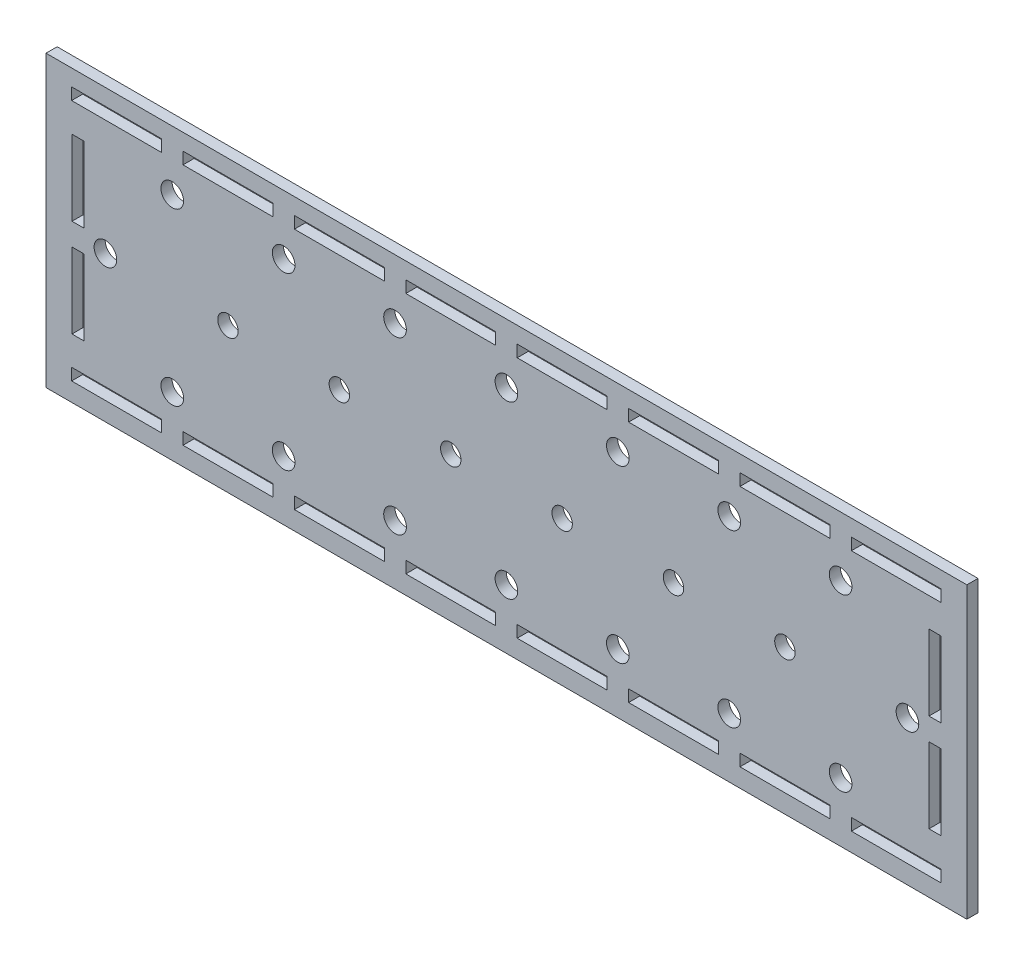
SolidWorks part; units mm, degrees
ref_plane "Front Plane" through (0, 0, 0) normal (0, 0, 1) x (1, 0, 0)
ref_plane "Top Plane" through (0, 0, 0) normal (0, 1, 0) x (1, 0, 0)
ref_plane "Right Plane" through (0, 0, 0) normal (1, 0, 0) x (0, 0, -1)
sketch "Sketch1" plane through (0, 0, 0) normal (0, 0, 1) x (-1, 0, 0)
  line L0 (-395.8872, 493) -> (-395.8872, 489.8)
  line L2 (-395.8872, 493) -> (-371.6872, 493)
  line L3 (-371.6872, 493) -> (-371.6872, 489.8)
  line L4 (-395.8872, 489.8) -> (-371.6872, 489.8)
  line L8 (-425.8872, 493) -> (-425.8872, 489.8)
  line L9 (-552.7872, 498) -> (-304.7872, 498)
  line L10 (-552.7872, 498) -> (-552.7872, 420)
  line L11 (-552.7872, 420) -> (-304.7872, 420)
  line L12 (-304.7872, 498) -> (-304.7872, 420)
  line L13 (-365.8872, 493) -> (-341.6872, 493)
  line L14 (-365.8872, 493) -> (-365.8872, 489.8)
  line L15 (-365.8872, 489.8) -> (-341.6872, 489.8)
  line L16 (-341.6872, 493) -> (-341.6872, 489.8)
  line L17 (-425.8872, 493) -> (-401.6872, 493)
  line L18 (-401.6872, 493) -> (-401.6872, 489.8)
  line L19 (-425.8872, 489.8) -> (-401.6872, 489.8)
  line L20 (-455.8872, 493) -> (-455.8872, 489.8)
  line L21 (-455.8872, 493) -> (-431.6872, 493)
  line L22 (-431.6872, 493) -> (-431.6872, 489.8)
  line L23 (-455.8872, 489.8) -> (-431.6872, 489.8)
  line L24 (-485.8872, 493) -> (-485.8872, 489.8)
  line L25 (-485.8872, 493) -> (-461.6872, 493)
  line L26 (-461.6872, 493) -> (-461.6872, 489.8)
  line L27 (-485.8872, 489.8) -> (-461.6872, 489.8)
  line L28 (-515.8872, 493) -> (-515.8872, 489.8)
  line L29 (-515.8872, 493) -> (-491.6872, 493)
  line L30 (-491.6872, 493) -> (-491.6872, 489.8)
  line L31 (-515.8872, 489.8) -> (-491.6872, 489.8)
  line L32 (-545.8872, 493) -> (-545.8872, 489.8)
  line L33 (-545.8872, 493) -> (-521.6872, 493)
  line L34 (-521.6872, 493) -> (-521.6872, 489.8)
  line L35 (-545.8872, 489.8) -> (-521.6872, 489.8)
  line L36 (-335.8872, 493) -> (-335.8872, 489.8)
  line L37 (-335.8872, 493) -> (-311.6872, 493)
  line L38 (-311.6872, 493) -> (-311.6872, 489.8)
  line L39 (-335.8872, 489.8) -> (-311.6872, 489.8)
  line L40 (-552.7872, 459) -> (-513.2251, 459) construction
  line L73 (-314.9872, 455.7) -> (-311.7872, 455.7)
  line L74 (-314.9872, 482) -> (-311.7872, 482)
  line L75 (-314.9872, 482) -> (-314.9872, 461.7)
  line L76 (-314.9872, 461.7) -> (-311.7872, 461.7)
  line L77 (-311.7872, 482) -> (-311.7872, 461.7)
  line L78 (-311.7872, 435.4) -> (-311.7872, 455.7)
  line L79 (-314.9872, 435.4) -> (-311.7872, 435.4)
  line L80 (-314.9872, 435.4) -> (-314.9872, 455.7)
  line L81 (-428.7872, 510.2561) -> (-428.7872, 380.3241) construction
  line L82 (-542.5872, 435.4) -> (-542.5872, 455.7)
  line L83 (-542.5872, 435.4) -> (-545.7872, 435.4)
  line L84 (-545.7872, 435.4) -> (-545.7872, 455.7)
  line L85 (-542.5872, 455.7) -> (-545.7872, 455.7)
  line L86 (-542.5872, 461.7) -> (-545.7872, 461.7)
  line L87 (-545.7872, 482) -> (-545.7872, 461.7)
  line L88 (-542.5872, 482) -> (-545.7872, 482)
  line L89 (-542.5872, 482) -> (-542.5872, 461.7)
  line L90 (-545.8872, 424.4) -> (-521.6872, 424.4)
  line L91 (-521.6872, 424.4) -> (-521.6872, 427.6)
  line L92 (-545.8872, 427.6) -> (-521.6872, 427.6)
  line L93 (-545.8872, 424.4) -> (-545.8872, 427.6)
  line L94 (-515.8872, 424.4) -> (-491.6872, 424.4)
  line L95 (-491.6872, 424.4) -> (-491.6872, 427.6)
  line L96 (-515.8872, 427.6) -> (-491.6872, 427.6)
  line L97 (-515.8872, 424.4) -> (-515.8872, 427.6)
  line L98 (-485.8872, 424.4) -> (-461.6872, 424.4)
  line L99 (-461.6872, 424.4) -> (-461.6872, 427.6)
  line L100 (-485.8872, 427.6) -> (-461.6872, 427.6)
  line L101 (-485.8872, 424.4) -> (-485.8872, 427.6)
  line L102 (-455.8872, 424.4) -> (-431.6872, 424.4)
  line L103 (-431.6872, 424.4) -> (-431.6872, 427.6)
  line L104 (-455.8872, 427.6) -> (-431.6872, 427.6)
  line L105 (-455.8872, 424.4) -> (-455.8872, 427.6)
  line L106 (-425.8872, 424.4) -> (-401.6872, 424.4)
  line L107 (-401.6872, 424.4) -> (-401.6872, 427.6)
  line L108 (-425.8872, 427.6) -> (-401.6872, 427.6)
  line L109 (-425.8872, 424.4) -> (-425.8872, 427.6)
  line L110 (-395.8872, 424.4) -> (-371.6872, 424.4)
  line L111 (-371.6872, 424.4) -> (-371.6872, 427.6)
  line L112 (-395.8872, 427.6) -> (-371.6872, 427.6)
  line L113 (-395.8872, 424.4) -> (-395.8872, 427.6)
  line L114 (-365.8872, 427.6) -> (-341.6872, 427.6)
  line L115 (-341.6872, 424.4) -> (-341.6872, 427.6)
  line L116 (-365.8872, 424.4) -> (-341.6872, 424.4)
  line L117 (-365.8872, 424.4) -> (-365.8872, 427.6)
  line L118 (-335.8872, 424.4) -> (-311.6872, 424.4)
  line L119 (-311.6872, 424.4) -> (-311.6872, 427.6)
  line L120 (-335.8872, 427.6) -> (-311.6872, 427.6)
  line L121 (-335.8872, 424.4) -> (-335.8872, 427.6)
  circle A16 centre (-338.7872, 436) radius 3.05
  circle A17 centre (-368.7872, 436) radius 3.05
  circle A18 centre (-428.7872, 436) radius 3.05
  circle A19 centre (-398.7872, 436) radius 3.05
  circle A20 centre (-488.7872, 436) radius 3.05
  circle A21 centre (-458.7872, 436) radius 3.05
  circle A22 centre (-458.7872, 482) radius 3.05
  circle A23 centre (-428.7872, 482) radius 3.05
  circle A24 centre (-398.7872, 482) radius 3.05
  circle A25 centre (-368.7872, 482) radius 3.05
  circle A26 centre (-338.7872, 482) radius 3.05
  circle A27 centre (-320.7872, 458.7) radius 3.05
  circle A28 centre (-488.7872, 482) radius 3.05
  circle A29 centre (-518.7872, 436) radius 3.05
  circle A30 centre (-536.7872, 459) radius 3.05
  circle A31 centre (-518.7872, 482) radius 3.05
  point P107 (-313.3872, 482)
  dimension "D4" = 16
  dimension "D11" = 3
  dimension "D1" = 16
  dimension "D2" = 16
  dimension "D3" = 7
  dimension "D5" = 2.9
  dimension "D6" = 2.9
  dimension "D7" = 5
  dimension "D8" = 3.2
  dimension "D14" = 3.2
  dimension "D9" = 7
  dimension "D10" = 2
extrude "Boss-Extrude2" add sketch "Sketch1" along normal blind 3
sketch "Sketch4" plane through (545.7872, 0, 0) normal (-1, 0, 0) x (0, 0, 1)
  line L0 (3, -427.6) -> (10, -427.6)
  line L3 (3, -427.6) -> (3, -435.4)
  line L4 (0, -435.4) -> (0, -455.7)
  line L5 (0, -455.7) -> (3, -455.7)
  line L6 (3, -455.7) -> (3, -435.4)
  line L7 (3, -435.4) -> (0, -435.4)
  line L8 (0, -435.4) -> (0, -455.7)
  line L9 (0, -455.7) -> (3, -455.7)
  line L11 (3, -435.4) -> (0, -435.4)
  line L12 (0, -461.7) -> (0, -482)
  line L13 (0, -482) -> (3, -482)
  line L14 (3, -482) -> (3, -461.7)
  line L15 (3, -461.7) -> (0, -461.7)
  line L17 (0, -482) -> (3, -482)
  line L19 (3, -461.7) -> (0, -461.7)
  line L20 (10, -427.6) -> (10, -489.8)
  line L22 (3, -455.7) -> (3, -461.7)
  line L23 (0, -461.7) -> (0, -482)
  line L24 (3, -482) -> (3, -489.8)
  line L25 (3, -489.8) -> (10, -489.8)
  dimension "D1" = 0
  dimension "D2" = 0
sketch "Sketch5" plane through (0, 0, 3) normal (0, 0, 1) x (1, 0, 0)
  line L0 (304.7872, -459) -> (418.6213, -459) construction
  line L1 (304.7872, -420) -> (304.7872, -498) construction
  circle A0 centre (353.7872, -459) radius 2.75
  circle A2 centre (338.7872, -436) radius 3.05 construction
  circle A4 centre (383.7872, -459) radius 2.75
  circle A5 centre (413.7872, -459) radius 2.75
  circle A6 centre (443.7872, -459) radius 2.75
  circle A7 centre (473.7872, -459) radius 2.75
  circle A8 centre (503.7872, -459) radius 2.75
  dimension "D1" = 15
  dimension "D2" = 5.5
  dimension "D3" = 6
extrude "Cut-Extrude1" cut sketch "Sketch5" against normal blind 10
